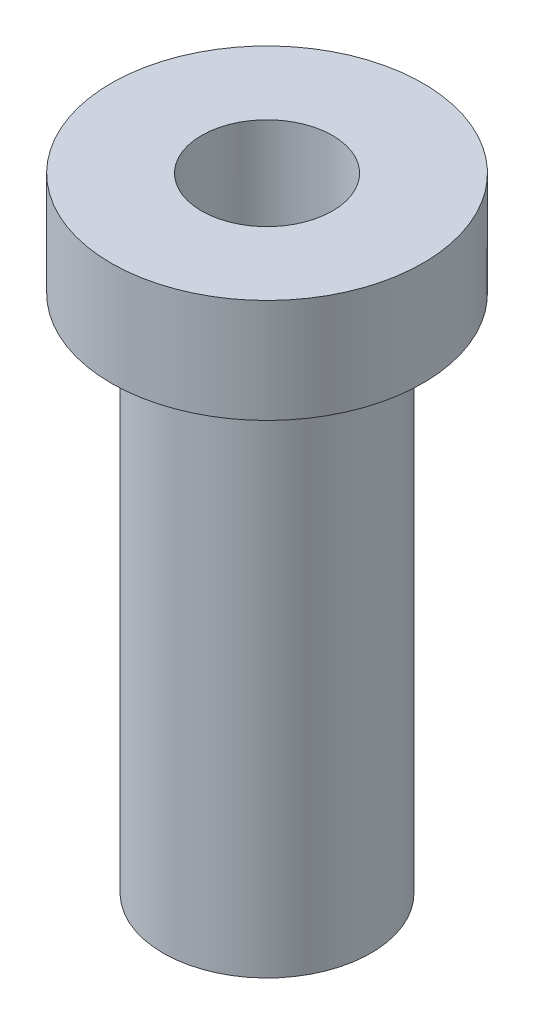
SolidWorks part; units mm, degrees
ref_plane "Front Plane" through (0, 0, 0) normal (0, 0, 1) x (1, 0, 0)
ref_plane "Top Plane" through (0, 0, 0) normal (0, 1, 0) x (1, 0, 0)
ref_plane "Right Plane" through (0, 0, 0) normal (1, 0, 0) x (0, 0, -1)
sketch "Sketch1" plane through (0, 0, 0) normal (0, 1, 0) x (1, 0, 0)
  circle A0 centre (0, 0) radius 19.05
  circle A1 centre (0, 0) radius 8.001
  dimension "D1" = 38.1
  dimension "D2" = 16.002
extrude "Boss-Extrude2" add sketch "Sketch1" along normal blind 12.7 contours A0 | A1
sketch "Sketch2" plane through (0, 0, 0) normal (0, -1, 0) x (1, 0, 0)
  circle A0 centre (0, 0) radius 8.001
  circle A1 centre (0, 0) radius 12.7
  dimension "D1" = 25.4
  dimension "D2" = 16.002
extrude "Boss-Extrude3" add sketch "Sketch2" along normal blind 63.5
